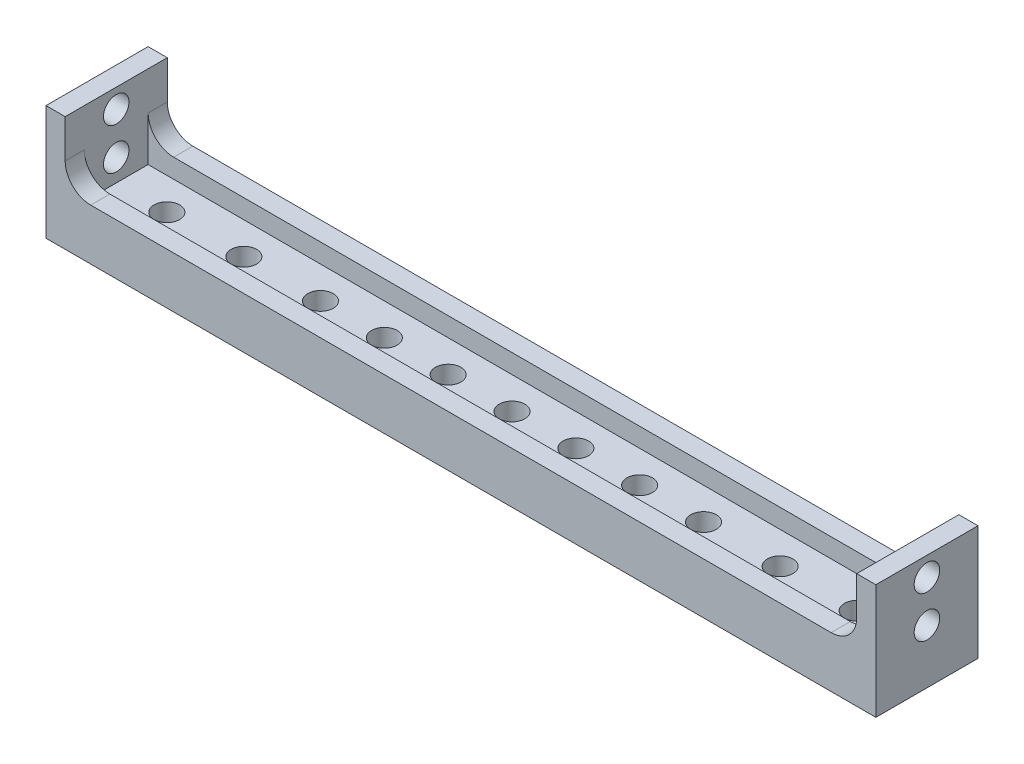
SolidWorks part; units mm, degrees
ref_plane "Front Plane" through (0, 0, 0) normal (0, 0, 1) x (1, 0, 0)
ref_plane "Top Plane" through (0, 0, 0) normal (0, 1, 0) x (1, 0, 0)
ref_plane "Right Plane" through (0, 0, 0) normal (1, 0, 0) x (0, 0, -1)
sketch "Sketch1" plane through (0, 0, 0) normal (0, 1, 0) x (1, 0, 0)
  line L1 (65, 8) -> (-65, 8)
  line L2 (65, 8) -> (65, -8)
  line L3 (65, -8) -> (-65, -8)
  line L4 (-65, 8) -> (-65, -8)
  line L5 (65, 8) -> (-65, -8) construction
  line L6 (65, -8) -> (-65, 8) construction
  point P0 (0, 0)
extrude "Boss-Extrude1" add sketch "Sketch1" along normal blind 5
sketch "Sketch2" plane through (0, 5, 0) normal (0, 1, 0) x (1, 0, 0)
  line L0 (-62, 5) -> (62, 5)
  line L1 (-65, 8) -> (65, 8)
  line L2 (-65, 8) -> (-65, -8)
  line L3 (-65, -8) -> (65, -8)
  line L4 (65, 8) -> (65, -8)
  line L5 (62, 5) -> (62, -5)
  line L6 (-62, -5) -> (62, -5)
  line L7 (-62, 5) -> (-62, -5)
  dimension "D1" = 3
extrude "Boss-Extrude2" add sketch "Sketch2" along normal blind 3
sketch "Sketch3" plane through (0, 8, 0) normal (0, 1, 0) x (1, 0, 0)
  line L0 (-65, -8) -> (65, -8) construction
  line L1 (-65, 8) -> (-62, 8)
  line L2 (-65, 8) -> (-65, -8)
  line L3 (-65, -8) -> (-62, -8)
  line L4 (-62, 8) -> (-62, -8)
  line L6 (65, 8) -> (62, 8)
  line L7 (65, 8) -> (65, -8)
  line L8 (65, -8) -> (62, -8)
  line L9 (62, 8) -> (62, -8)
extrude "Boss-Extrude3" add sketch "Sketch3" along normal blind 10
fillet "Fillet1" radius 4 4 edges at (62, 8, 6.5) (62, 8, -6.5) (-62, 8, 6.5) (-62, 8, -6.5)
sketch "Sketch4" plane through (0, 5, 0) normal (0, 1, 0) x (1, 0, 0)
  circle A0 centre (42, 0) radius 2
  circle A1 centre (-42, 0) radius 2
extrude "Cut-Extrude1" cut sketch "Sketch4" against normal blind 10
sketch "Sketch6" plane through (0, 0, 0) normal (0, -1, 0) x (1, 0, 0)
  circle A0 centre (42, 0) radius 4
  circle A1 centre (-42, 0) radius 4
extrude "Cut-Extrude2" cut sketch "Sketch6" against normal blind 2
sketch "Sketch7" plane through (0, 5, 0) normal (0, 1, 0) x (1, 0, 0)
  circle A0 centre (0, 0) radius 2
  circle A1 centre (-10, 0) radius 2
  circle A2 centre (-20, 0) radius 2
  circle A3 centre (-30, 0) radius 2
  circle A7 centre (-40, 0) radius 2 [skipped]
  circle A8 centre (-60, 0) radius 2 [skipped]
  circle A9 centre (-50, 0) radius 2 [skipped]
  circle A10 centre (-54.0664, 0) radius 2
  circle A11 centre (54.0664, 0) radius 2
  circle A12 centre (30, 0) radius 2
  circle A13 centre (20, 0) radius 2
  circle A14 centre (10, 0) radius 2
  dimension "D1" = 7
extrude "Cut-Extrude3" cut sketch "Sketch7" against normal up to surface (5 mm away) up to face at (42, 0, -4)
sketch "Sketch8" plane through (-62, 0, 0) normal (1, 0, 0) x (0, 0, -1)
  circle A0 centre (0, 8.5) radius 2
  circle A1 centre (0, 15) radius 2
extrude "Cut-Extrude4" cut sketch "Sketch8" against normal through all both and the other way through all contours A1 | A0
